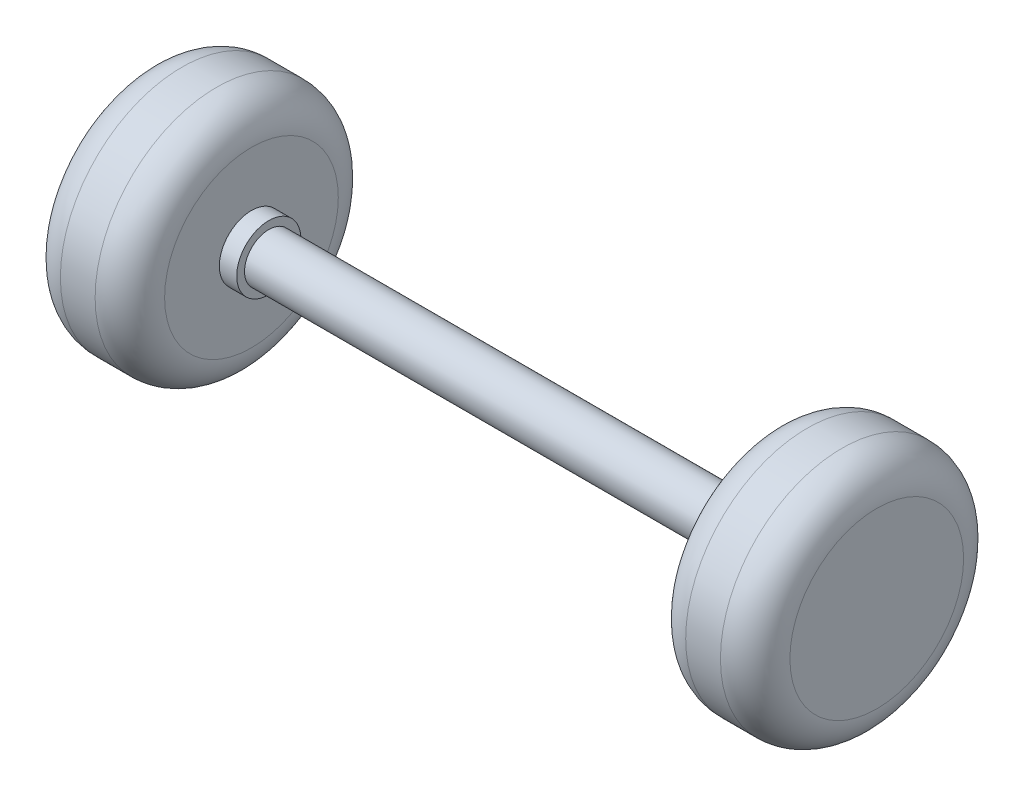
SolidWorks part; units mm, degrees
material "ABS"
ref_plane "Front Plane" through (0, 0, 0) normal (0, 0, 1) x (1, 0, 0)
ref_plane "Top Plane" through (0, 0, 0) normal (0, 1, 0) x (1, 0, 0)
ref_plane "Right Plane" through (0, 0, 0) normal (1, 0, 0) x (0, 0, -1)
sketch "Sketch1" plane through (0, 0, 0) normal (1, 0, 0) x (0, 0, -1)
  circle A0 centre (0, 0) radius 17.78
  dimension "D1" = 35.56
extrude "Boss-Extrude1" add sketch "Sketch1" along normal mid plane 355.6
ref_point "Point2"
sketch "Sketch9" plane through (177.8, 0, 0) normal (1, 0, 0) x (0, 0, -1)
  circle A0 centre (0, 0) radius 23.495
extrude "Boss-Extrude4" add sketch "Sketch9" along normal blind 12.7
ref_point "Point3"
mirror "Mirror5" about plane through (0, 0, 0) normal (1, 0, 0) of "Boss-Extrude4"
mirror "Mirror6" about plane through (0, 0, 0) normal (0, 0, 1) of "Mirror5"
mirror "Mirror7" about plane through (0, 0, 0) normal (0, 0, 1) of "Mirror6"
sketch "Sketch13" plane through (190.5, 0, 0) normal (1, 0, 0) x (0, 0, -1)
  circle A0 centre (0, 0) radius 88.9
  dimension "D1" = 177.8
extrude "Boss-Extrude6" add sketch "Sketch13" along normal blind 76.2
fillet "Fillet3" radius 25.4 1 edges at (266.7, 0, -88.9)
fillet "Fillet4" radius 25.4 1 edges at (190.5, 0, -88.9)
mirror "Mirror11" about plane through (0, 0, 0) normal (1, 0, 0) of "Fillet4", "Fillet3", "Boss-Extrude6"
